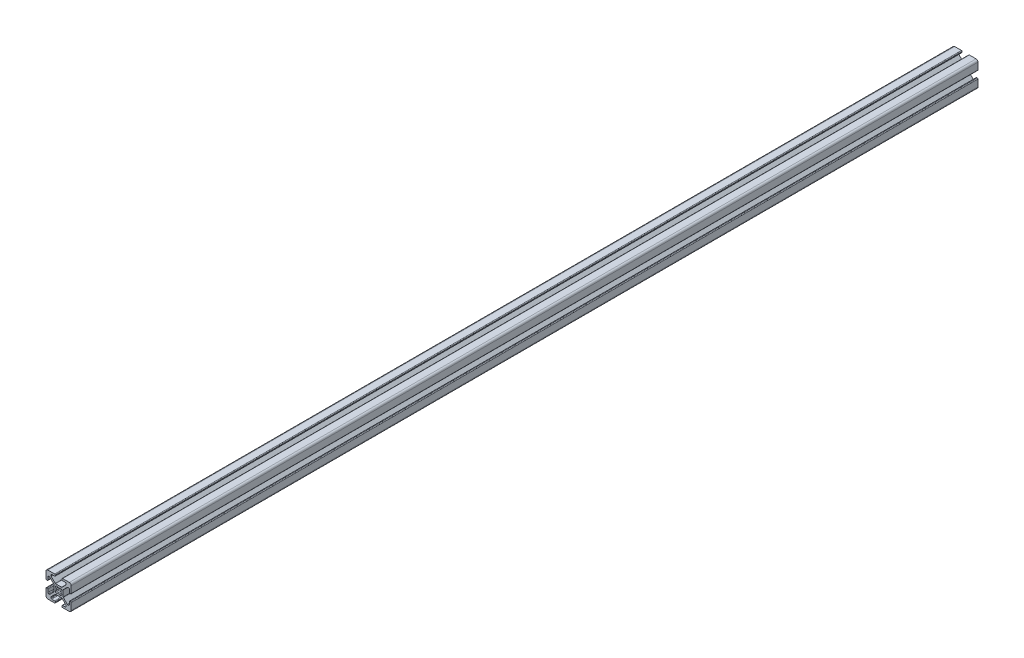
SolidWorks part; units mm, degrees
ref_plane "Front Plane" through (0, 0, 0) normal (0, 0, 1) x (1, 0, 0)
ref_plane "Top Plane" through (0, 0, 0) normal (0, 1, 0) x (1, 0, 0)
ref_plane "Right Plane" through (0, 0, 0) normal (1, 0, 0) x (0, 0, -1)
sketch "Sketch1" plane through (0, 0, 0) normal (0, 0, 1) x (1, 0, 0)
  line L0 (-5.0323, -0.3411) -> (-5.5163, -0.3411)
  line L1 (-6.0243, 0.1669) -> (-6.0243, 2.5159)
  line L2 (-4.5243, 0.1669) -> (-4.5243, 5.5289)
  line L3 (-10.8693, -5.355) -> (-10.8693, -0.5871)
  line L4 (-7.2582, 3.0239) -> (-6.5323, 3.0239)
  line L5 (-7.6174, 2.8752) -> (-10.7205, -0.2279)
  line L6 (-5.0323, -5.6011) -> (-5.5163, -5.6011)
  line L7 (-4.5243, -6.1091) -> (-4.5243, -11.4711)
  line L8 (-6.0243, -6.1091) -> (-6.0243, -8.4581)
  line L9 (-7.2582, -8.9661) -> (-6.5323, -8.9661)
  line L10 (-7.6174, -8.8173) -> (-10.7205, -5.7142)
  line L11 (-12.3994, -5.2756) -> (-12.2198, -5.096)
  line L12 (-17.1543, 6.5209) -> (-17.1543, 6.0369)
  line L13 (-17.6623, 7.0289) -> (-23.0243, 7.0289)
  line L14 (-17.6623, 5.5289) -> (-20.0113, 5.5289)
  line L15 (-12.1404, 0.6839) -> (-16.9082, 0.6839)
  line L16 (-20.5193, 4.295) -> (-20.5193, 5.0209)
  line L17 (-20.3705, 3.9358) -> (-17.2674, 0.8327)
  line L18 (-11.8943, 6.5209) -> (-11.8943, 6.0369)
  line L19 (-11.3863, 7.0289) -> (-6.0243, 7.0289)
  line L20 (-11.3863, 5.5289) -> (-9.0373, 5.5289)
  line L21 (-8.5293, 4.295) -> (-8.5293, 5.0209)
  line L22 (-8.6781, 3.9358) -> (-11.7812, 0.8327)
  line L23 (-12.2198, -0.8462) -> (-12.3994, -0.6666)
  line L24 (-24.0163, -5.6011) -> (-23.5323, -5.6011)
  line L25 (-24.5243, -6.1091) -> (-24.5243, -11.4711)
  line L26 (-23.0243, -6.1091) -> (-23.0243, -8.4581)
  line L27 (-18.1793, -0.5871) -> (-18.1793, -5.355)
  line L28 (-21.7904, -8.9661) -> (-22.5163, -8.9661)
  line L29 (-21.4312, -8.8173) -> (-18.3281, -5.7142)
  line L30 (-24.0163, -0.3411) -> (-23.5323, -0.3411)
  line L31 (-24.5243, 0.1669) -> (-24.5243, 5.5289)
  line L32 (-23.0243, 0.1669) -> (-23.0243, 2.5159)
  line L33 (-21.7904, 3.0239) -> (-22.5163, 3.0239)
  line L34 (-21.4312, 2.8752) -> (-18.3281, -0.2279)
  line L35 (-16.6492, -0.6666) -> (-16.8288, -0.8462)
  line L36 (-11.8943, -12.4631) -> (-11.8943, -11.9791)
  line L37 (-11.3863, -12.9711) -> (-6.0243, -12.9711)
  line L38 (-11.3863, -11.4711) -> (-9.0373, -11.4711)
  line L39 (-16.9082, -6.6261) -> (-12.1404, -6.6261)
  line L40 (-8.5293, -10.2371) -> (-8.5293, -10.9631)
  line L41 (-8.6781, -9.8779) -> (-11.7812, -6.7748)
  line L42 (-17.1543, -12.4631) -> (-17.1543, -11.9791)
  line L43 (-17.6623, -12.9711) -> (-23.0243, -12.9711)
  line L44 (-17.6623, -11.4711) -> (-20.0113, -11.4711)
  line L45 (-20.5193, -10.2371) -> (-20.5193, -10.9631)
  line L46 (-20.3705, -9.8779) -> (-17.2674, -6.7748)
  line L47 (-16.8288, -5.096) -> (-16.6492, -5.2756)
  arc A0 (-15.3283, -4.9062) -> (-13.7203, -4.9062) centre (-14.5243, -2.9711) ccw
  arc A1 (-6.0243, 2.5159) -> (-6.5323, 3.0239) centre (-6.5323, 2.5159) ccw
  arc A2 (-7.2582, 3.0239) -> (-7.6174, 2.8752) centre (-7.2582, 2.5159) ccw
  arc A3 (-10.7205, -0.2279) -> (-10.8693, -0.5871) centre (-10.3613, -0.5871) ccw
  arc A4 (-10.8693, -5.355) -> (-10.7205, -5.7142) centre (-10.3613, -5.355) ccw
  arc A5 (-7.6174, -8.8173) -> (-7.2582, -8.9661) centre (-7.2582, -8.4581) ccw
  arc A6 (-6.5323, -8.9661) -> (-6.0243, -8.4581) centre (-6.5323, -8.4581) ccw
  arc A7 (-5.5163, -5.6011) -> (-6.0243, -6.1091) centre (-5.5163, -6.1091) ccw
  arc A8 (-4.5243, -6.1091) -> (-5.0323, -5.6011) centre (-5.0323, -6.1091) ccw
  arc A9 (-5.0323, -0.3411) -> (-4.5243, 0.1669) centre (-5.0323, 0.1669) ccw
  arc A10 (-6.0243, 0.1669) -> (-5.5163, -0.3411) centre (-5.5163, 0.1669) ccw
  arc A11 (-13.7203, -4.9062) -> (-12.3994, -5.2756) centre (-12.9559, -4.7191) ccw
  arc A12 (-12.2198, -5.096) -> (-12.5892, -3.775) centre (-12.7763, -4.5395) ccw
  arc A13 (-17.1543, 6.5209) -> (-17.6623, 7.0289) centre (-17.6623, 6.5209) ccw
  arc A14 (-17.6623, 5.5289) -> (-17.1543, 6.0369) centre (-17.6623, 6.0369) ccw
  arc A15 (-12.5892, -3.775) -> (-12.5892, -2.1671) centre (-14.5243, -2.9711) ccw
  arc A16 (-17.2674, 0.8327) -> (-16.9082, 0.6839) centre (-16.9082, 1.1919) ccw
  arc A17 (-20.0113, 5.5289) -> (-20.5193, 5.0209) centre (-20.0113, 5.0209) ccw
  arc A18 (-20.5193, 4.295) -> (-20.3705, 3.9358) centre (-20.0113, 4.295) ccw
  arc A19 (-11.8943, 6.0369) -> (-11.3863, 5.5289) centre (-11.3863, 6.0369) ccw
  arc A20 (-11.3863, 7.0289) -> (-11.8943, 6.5209) centre (-11.3863, 6.5209) ccw
  arc A21 (-8.5293, 5.0209) -> (-9.0373, 5.5289) centre (-9.0373, 5.0209) ccw
  arc A22 (-8.6781, 3.9358) -> (-8.5293, 4.295) centre (-9.0373, 4.295) ccw
  arc A23 (-12.1404, 0.6839) -> (-11.7812, 0.8327) centre (-12.1404, 1.1919) ccw
  arc A24 (-12.5892, -2.1671) -> (-12.2198, -0.8462) centre (-12.7763, -1.4027) ccw
  arc A25 (-12.3994, -0.6666) -> (-13.7203, -1.0359) centre (-12.9559, -1.223) ccw
  arc A26 (-24.0163, -5.6011) -> (-24.5243, -6.1091) centre (-24.0163, -6.1091) ccw
  arc A27 (-23.0243, -6.1091) -> (-23.5323, -5.6011) centre (-23.5323, -6.1091) ccw
  arc A28 (-13.7203, -1.0359) -> (-15.3283, -1.0359) centre (-14.5243, -2.9711) ccw
  arc A29 (-18.3281, -5.7142) -> (-18.1793, -5.355) centre (-18.6873, -5.355) ccw
  arc A30 (-23.0243, -8.4581) -> (-22.5163, -8.9661) centre (-22.5163, -8.4581) ccw
  arc A31 (-21.7904, -8.9661) -> (-21.4312, -8.8173) centre (-21.7904, -8.4581) ccw
  arc A32 (-23.5323, -0.3411) -> (-23.0243, 0.1669) centre (-23.5323, 0.1669) ccw
  arc A33 (-24.5243, 0.1669) -> (-24.0163, -0.3411) centre (-24.0163, 0.1669) ccw
  arc A34 (-22.5163, 3.0239) -> (-23.0243, 2.5159) centre (-22.5163, 2.5159) ccw
  arc A35 (-21.4312, 2.8752) -> (-21.7904, 3.0239) centre (-21.7904, 2.5159) ccw
  arc A36 (-18.1793, -0.5871) -> (-18.3281, -0.2279) centre (-18.6873, -0.5871) ccw
  arc A37 (-15.3283, -1.0359) -> (-16.6492, -0.6666) centre (-16.0927, -1.223) ccw
  arc A38 (-16.8288, -0.8462) -> (-16.4594, -2.1671) centre (-16.2723, -1.4027) ccw
  arc A39 (-11.8943, -12.4631) -> (-11.3863, -12.9711) centre (-11.3863, -12.4631) ccw
  arc A40 (-11.3863, -11.4711) -> (-11.8943, -11.9791) centre (-11.3863, -11.9791) ccw
  arc A41 (-16.4594, -2.1671) -> (-16.4594, -3.775) centre (-14.5243, -2.9711) ccw
  arc A42 (-11.7812, -6.7748) -> (-12.1404, -6.6261) centre (-12.1404, -7.1341) ccw
  arc A43 (-9.0373, -11.4711) -> (-8.5293, -10.9631) centre (-9.0373, -10.9631) ccw
  arc A44 (-8.5293, -10.2371) -> (-8.6781, -9.8779) centre (-9.0373, -10.2371) ccw
  arc A45 (-17.1543, -11.9791) -> (-17.6623, -11.4711) centre (-17.6623, -11.9791) ccw
  arc A46 (-17.6623, -12.9711) -> (-17.1543, -12.4631) centre (-17.6623, -12.4631) ccw
  arc A47 (-20.5193, -10.9631) -> (-20.0113, -11.4711) centre (-20.0113, -10.9631) ccw
  arc A48 (-20.3705, -9.8779) -> (-20.5193, -10.2371) centre (-20.0113, -10.2371) ccw
  arc A49 (-16.9082, -6.6261) -> (-17.2674, -6.7748) centre (-16.9082, -7.1341) ccw
  arc A50 (-16.4594, -3.775) -> (-16.8288, -5.096) centre (-16.2723, -4.5395) ccw
  arc A51 (-16.6492, -5.2756) -> (-15.3283, -4.9062) centre (-16.0927, -4.7191) ccw
  arc A52 (-4.5243, 5.5289) -> (-6.0243, 7.0289) centre (-6.0243, 5.5289) ccw
  arc A53 (-6.0243, -12.9711) -> (-4.5243, -11.4711) centre (-6.0243, -11.4711) ccw
  arc A54 (-24.5243, -11.4711) -> (-23.0243, -12.9711) centre (-23.0243, -11.4711) ccw
  arc A55 (-23.0243, 7.0289) -> (-24.5243, 5.5289) centre (-23.0243, 5.5289) ccw
extrude "Extrude1" add sketch "Sketch1" along normal blind 720
